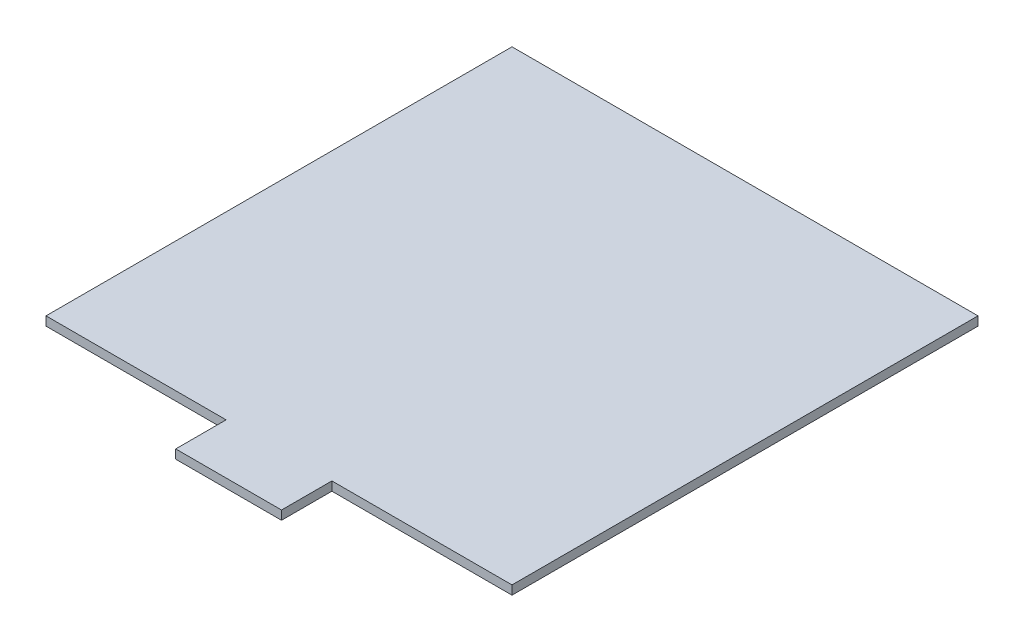
SolidWorks part; units mm, degrees
material "PET"
ref_plane "Front Plane" through (0, 0, 0) normal (0, 0, 1) x (1, 0, 0)
ref_plane "Top Plane" through (0, 0, 0) normal (0, 1, 0) x (1, 0, 0)
ref_plane "Right Plane" through (0, 0, 0) normal (1, 0, 0) x (0, 0, -1)
sketch "Sketch1" plane through (0, 0, 0) normal (0, 1, 0) x (1, 0, 0)
  line L1 (-19.5, -19.5) -> (19.5, -19.5)
  line L2 (-19.5, -19.5) -> (-19.5, 19.5)
  line L3 (-19.5, 19.5) -> (19.5, 19.5)
  line L4 (19.5, -19.5) -> (19.5, 19.5)
  line L5 (-19.5, -19.5) -> (19.5, 19.5) construction
  line L6 (-19.5, 19.5) -> (19.5, -19.5) construction
  point P0 (0, 0)
  dimension "D1" = 39
extrude "Boss-Extrude1" add sketch "Sketch1" along normal blind 0.778
sketch "Sketch2" plane through (0, 0.778, 0) normal (0, 1, 0) x (1, 0, 0)
  line L0 (5.334, -23.495) -> (23.495, -23.495)
  line L1 (-23.495, -23.495) -> (-5.334, -23.495)
  line L2 (-23.495, -23.495) -> (-23.495, 23.495)
  line L3 (-23.495, 23.495) -> (23.495, 23.495)
  line L4 (23.495, -23.495) -> (23.495, 23.495)
  line L5 (-23.495, -23.495) -> (23.495, 23.495) construction
  line L6 (-23.495, 23.495) -> (23.495, -23.495) construction
  line L8 (-5.334, -23.495) -> (-5.334, -28.575)
  line L9 (-5.334, -28.575) -> (5.334, -28.575)
  line L10 (5.334, -23.495) -> (5.334, -28.575)
  point P0 (0, 0)
  dimension "D1" = 46.99
  dimension "D2" = 10.668
  dimension "D3" = 5.08
extrude "Boss-Extrude2" add sketch "Sketch2" along normal blind 0.9
fillet "Fillet1" radius 0.75 8 edges at (0, 0, -19.5) (-19.5, 0, 0) (0, 0, 19.5) (19.5, 0, 0) (19.5, 0.389, -19.5) (19.5, 0.389, 19.5) (-19.5, 0.389, 19.5) (-19.5, 0.389, -19.5)
sketch "Sketch3" plane through (0, 0.778, 0) normal (0, -1, 0) x (1, 0, 0)
  line L0 (-23.495, -23.495) -> (-23.495, 23.495) construction
  line L1 (-22.245, 22.245) -> (22.245, 22.245)
  line L2 (-22.245, 22.245) -> (-22.245, -22.245)
  line L3 (-22.245, -22.245) -> (22.245, -22.245)
  line L4 (22.245, 22.245) -> (22.245, -22.245)
  line L5 (23.495, 23.495) -> (23.495, -23.495) construction
  line L6 (5.334, 23.495) -> (23.495, 23.495) construction
  line L7 (23.495, -23.495) -> (-23.495, -23.495) construction
  line L8 (-21.245, 21.245) -> (21.245, 21.245)
  line L9 (21.245, 21.245) -> (21.245, -21.245)
  line L10 (-21.245, -21.245) -> (21.245, -21.245)
  line L11 (-21.245, 21.245) -> (-21.245, -21.245)
  dimension "D1" = 1.25
  dimension "D2" = 1.25
  dimension "D3" = 1.25
  dimension "D4" = 1.25
  dimension "D5" = 1
extrude "Cut-Extrude1" cut sketch "Sketch3" against normal blind 0.5 contours L4 L1 L2 L3 L11 L8 L9 L10
sketch "Sketch7" plane through (0, 0.778, 0) normal (0, -1, 0) x (1, 0, 0)
  line L0 (-18.75, 19.5) -> (18.75, 19.5) construction
  line L1 (-18.75, 19.5) -> (18.75, 19.5)
  line L2 (-19.5, -18.75) -> (-19.5, 18.75) construction
  line L3 (-19.5, -18.75) -> (-19.5, 18.75)
  line L4 (21.245, 21.245) -> (-21.245, 21.245)
  line L5 (-21.245, 21.245) -> (-21.245, -21.245)
  line L6 (-21.245, -21.245) -> (21.245, -21.245)
  line L7 (21.245, -21.245) -> (21.245, 21.245)
  line L8 (21.245, 21.245) -> (-21.245, 21.245)
  line L9 (-21.245, 21.245) -> (-21.245, -21.245)
  line L10 (-21.245, -21.245) -> (21.245, -21.245)
  line L11 (21.245, -21.245) -> (21.245, 21.245)
  line L12 (18.75, -19.5) -> (-18.75, -19.5) construction
  line L13 (18.75, -19.5) -> (-18.75, -19.5)
  line L14 (19.5, 18.75) -> (19.5, -18.75) construction
  line L15 (19.5, 18.75) -> (19.5, -18.75)
  arc A0 (18.75, 19.5) -> (19.5, 18.75) centre (18.75, 18.75) cw
  arc A1 (19.5, -18.75) -> (18.75, -19.5) centre (18.75, -18.75) cw
  arc A2 (-19.5, -18.75) -> (-18.75, -19.5) centre (-18.75, -18.75) ccw
  arc A3 (-18.75, 19.5) -> (-19.5, 18.75) centre (-18.75, 18.75) ccw
  dimension "D1" = 0
extrude "Boss-Extrude5" add sketch "Sketch7" along normal blind 0.5 separate body
